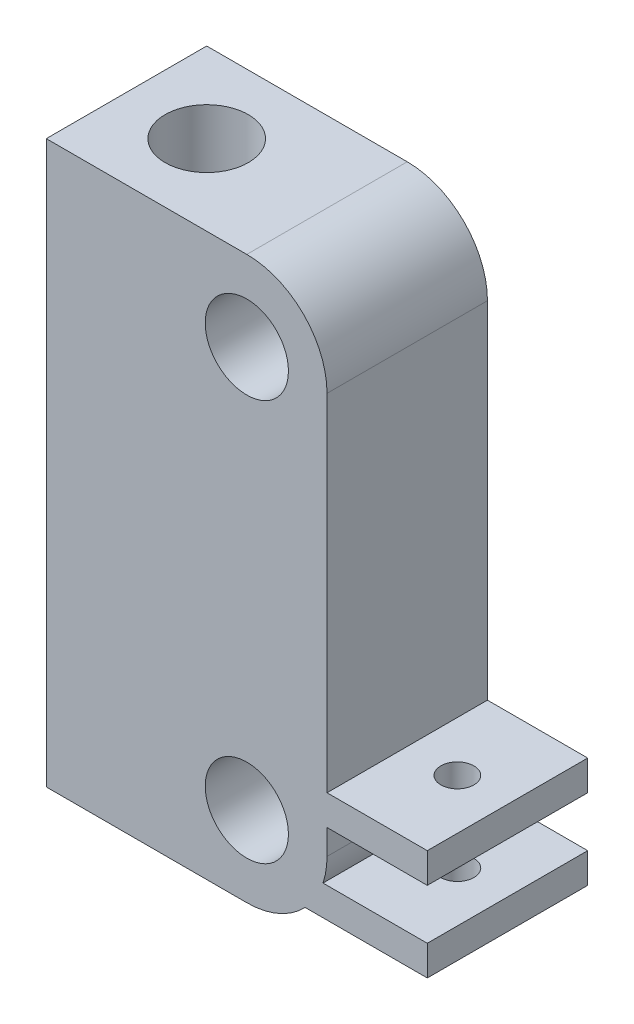
SolidWorks part; units mm, degrees
material "ABS"
ref_plane "Front Plane" through (0, 0, 0) normal (0, 0, 1) x (1, 0, 0)
ref_plane "Top Plane" through (0, 0, 0) normal (0, 1, 0) x (1, 0, 0)
ref_plane "Right Plane" through (0, 0, 0) normal (1, 0, 0) x (0, 0, -1)
sketch "Sketch1" plane through (0, 0, 0) normal (0, 0, 1) x (1, 0, 0)
  line L0 (11.942, -20.8688) -> (21.942, -20.8688)
  line L1 (-16.058, 21.6312) -> (3.942, 21.6312)
  line L2 (-16.058, 21.6312) -> (-16.058, -34.3688)
  line L3 (-16.058, -34.3688) -> (3.942, -34.3688)
  line L4 (11.942, 13.6312) -> (11.942, -20.8688)
  line L5 (21.942, -20.8688) -> (21.942, -23.8688)
  line L6 (21.942, -23.8688) -> (11.942, -23.8688)
  line L7 (9.7514, -31.8688) -> (21.942, -31.8688)
  line L8 (21.942, -31.8688) -> (21.942, -28.8688)
  line L9 (21.942, -28.8688) -> (11.5413, -28.8688)
  line L10 (11.942, -23.8688) -> (11.942, -26.3688)
  circle A0 centre (3.942, 13.6312) radius 4.15
  circle A1 centre (3.942, -26.3688) radius 4.15
  arc A2 (3.942, -34.3688) -> (9.7514, -31.8688) centre (3.942, -26.3688) ccw
  arc A3 (3.942, 21.6312) -> (11.942, 13.6312) centre (3.942, 13.6312) cw
  arc A4 (11.5413, -28.8688) -> (11.942, -26.3688) centre (3.942, -26.3688) ccw
  dimension "D2" = 8.3
  dimension "D8" = 8
  dimension "D3" = 40
  dimension "D4" = 8
  dimension "D5" = 8
  dimension "D6" = 8
  dimension "D7" = 8
  dimension "D9" = 28
  dimension "D10" = 3
  dimension "D11" = 3
  dimension "D12" = 2.5
  dimension "D13" = 5
  dimension "D14" = 10
extrude "Boss-Extrude1" add sketch "Sketch1" against normal blind 16
sketch "Sketch2" plane through (0, 21.6312, 0) normal (0, 1, 0) x (1, 0, 0)
  line L0 (3.942, 0) -> (-16.058, 0) construction
  line L1 (-16.058, 16) -> (-16.058, 0) construction
  circle A0 centre (-8.058, 8) radius 4.15
  dimension "D1" = 8.3
  dimension "D2" = 8
  dimension "D3" = 8
extrude "Cut-Extrude1" cut sketch "Sketch2" against normal through all
ref_point "Point1"
sketch "Sketch3" plane through (0, -20.8688, 0) normal (0, 1, 0) x (1, 0, 0)
  line L0 (21.942, 16) -> (21.942, 0) construction
  line L2 (21.942, 16) -> (11.942, 16) construction
  circle A0 centre (16.942, 8) radius 1.65
  dimension "D1" = 3.3
  dimension "D2" = 5
  dimension "D3" = 8
extrude "Cut-Extrude2" cut sketch "Sketch3" against normal through all
equation "\"rod_diameter\"= 8"
equation "\"rod_hole_thickness\"= 4"
equation "\"D2@Sketch1\" = \"rod_diameter\" + \"printed_hole_tolerance\""
equation "\"rod_radius\"= \"rod_diameter\" / 2"
equation "\"D4@Sketch1\"=\"rod_radius\"+\"rod_hole_thickness\""
equation "\"D5@Sketch1\"=\"rod_radius\"+\"rod_hole_thickness\""
equation "\"D6@Sketch1\"=\"rod_radius\"+\"rod_hole_thickness\""
equation "\"D7@Sketch1\"=\"rod_radius\"+\"rod_hole_thickness\""
equation "\"D8@Sketch1\"=\"rod_radius\"+\"rod_hole_thickness\""
equation "\"D9@Sketch1\"=\"rod_diameter\"*2 + \"rod_hole_thickness\"*3"
equation "\"D1@Boss-Extrude1\"= \"rod_diameter\" + \"rod_hole_thickness\" * 2"
equation "\"D1@Sketch2\"=\"rod_diameter\"+\"printed_hole_tolerance\""
equation "\"D2@Sketch2\"=\"rod_radius\"+\"rod_hole_thickness\""
equation "\"D3@Sketch2\" = \"rod_radius\" + \"rod_hole_thickness\""
equation "\"platter_diameter\"= 320"
equation "\"platter_radius\"= \"platter_diameter\" / 2"
equation "\"extruder_mount_hole_spacing\"= 75"
equation "\"arm_rod_spacing\"= 40"
equation "\"D3@Sketch1\"=\"arm_rod_spacing\""
equation "\"D2@Sketch3\" = \"D14@Sketch1\" / 2"
equation "\"D3@Sketch3\"= \"D1@Boss-Extrude1\" / 2"
equation "\"top_frame_spacing\"= 100"
equation "\"motor_level_rod_spacing\"= 15"
equation "\"linear_bearing_diameter\"= 15"
equation "\"z_rod_spacing\"= 75"
equation "\"z_drive_rod_offset\"= 12"
equation "\"platter_rod_spacing\"= 50"
equation "\"rod_nut_thickness\"= 6.5"
equation "\"rod_nut_inscribed_diameter\"= 13"
equation "\"z_height\"= 400"
equation "\"gear_pitch\"=2"
equation "\"r_gear_teeth\"= 450"
equation "\"theta_gear_teeth\"= 385"
equation "\"sheet_thickness\"=5.333"
equation "\"sheet_tab_hole_thickness\"= \"sheet_thickness\""
equation "\"sheet_tab_width\"= \"sheet_thickness\"*2"
equation "\"sheet_double_tab_width\"= 35"
equation "\"sheet_bolt_diameter\"= 3"
equation "\"sheet_bolt_length\"= 16"
equation "\"sheet_nut_diameter\"= 5.5"
equation "\"sheet_nut_thickness\"= 2.5"
equation "\"sheet_nut_depth\"= 10"
equation "\"bearing_outside_diameter\"= 22"
equation "\"bearing_thickness\"= 7"
equation "\"corner_part_thickness\"= \"sheet_thickness\" + \"bearing_thickness\""
equation "\"setscrew_nut_diameter\"= 6"
equation "\"setscrew_nut_thickness\"= 3"
equation "\"setscrew_bolt_diameter\"= 3"
equation "\"motor_shaft_diameter\"= 5.7"
equation "\"printed_hole_tolerance\"= 0.3"
equation "\"D1@Sketch3\"=\"sheet_bolt_diameter\"+\"printed_hole_tolerance\""
